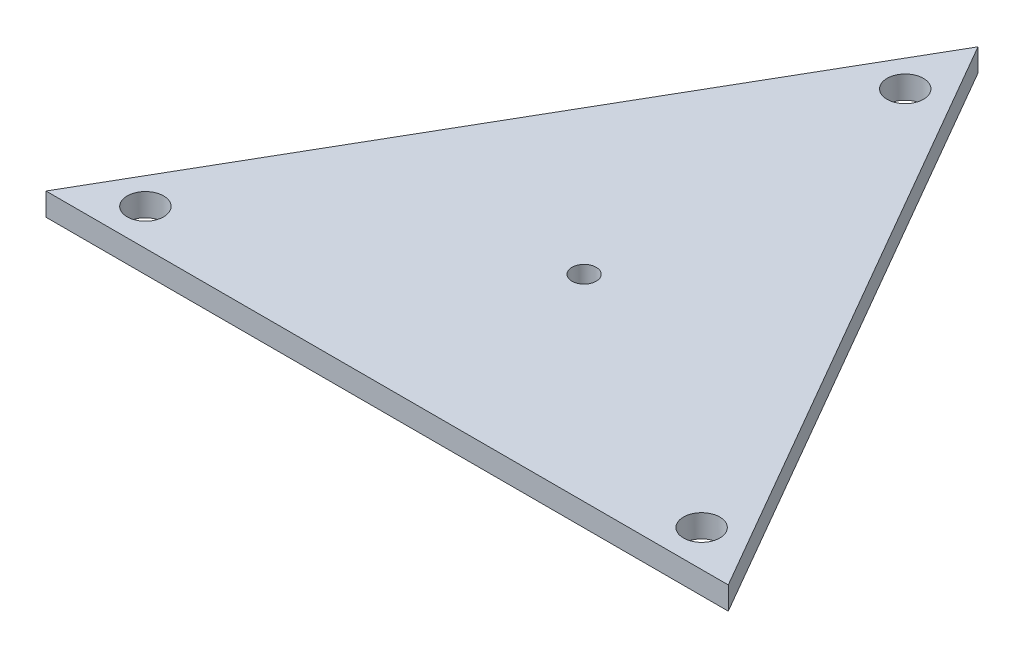
SolidWorks part; units mm, degrees
ref_plane "Front" through (0, 0, 0) normal (0, 0, 1) x (1, 0, 0)
ref_plane "Top" through (0, 0, 0) normal (0, 1, 0) x (1, 0, 0)
ref_plane "Right" through (0, 0, 0) normal (1, 0, 0) x (0, 0, -1)
sketch "Sketch1" plane through (0, 0, 0) normal (0, 1, 0) x (1, 0, 0)
  line L0 (0, 129.9038) -> (75, 0)
  line L1 (0, -55) -> (0, 55) construction
  line L2 (-55, 0) -> (55, 0) construction
  line L3 (75, 0) -> (-75, 0)
  line L4 (-75, 0) -> (0, 129.9038)
  line L5 (75, 0) -> (-37.5, 64.9519) construction
  line L6 (-75, 0) -> (37.5, 64.9519) construction
  line L7 (0, 129.9038) -> (0, 0) construction
  point P8 (0, 43.3013)
extrude "Boss-Extrude1" add sketch "Sketch1" along normal blind 5
sketch "Sketch2" plane through (0, 5, 0) normal (0, 1, 0) x (1, 0, 0)
  line L0 (0, -2.75) -> (0, 2.75) construction
  line L1 (-2.75, 0) -> (2.75, 0) construction
  line L2 (0, 129.9038) -> (-75, 0) construction
  line L3 (75, 0) -> (0, 129.9038) construction
  line L4 (0, 129.9038) -> (0, 0) construction
  line L5 (-75, 0) -> (37.5, 64.9519) construction
  line L6 (75, 0) -> (-37.5, 64.9519) construction
  circle A1 centre (-61.1436, 8) radius 4
  circle A2 centre (61.1436, 8) radius 4
  circle A3 centre (0, 113.9038) radius 4
  circle A4 centre (0, 43.3013) radius 2.6652 construction
  circle A5 centre (0, 43.3013) radius 2.6652
  dimension "D1" = 70.6025
  dimension "D2" = 8
  dimension "D6" = 122.2872
  dimension "D3" = 122.2872
  dimension "D4" = 70.6025
  dimension "D5" = 70.6025
extrude "Cut-Extrude1" cut sketch "Sketch2" against normal through all both and the other way through all
